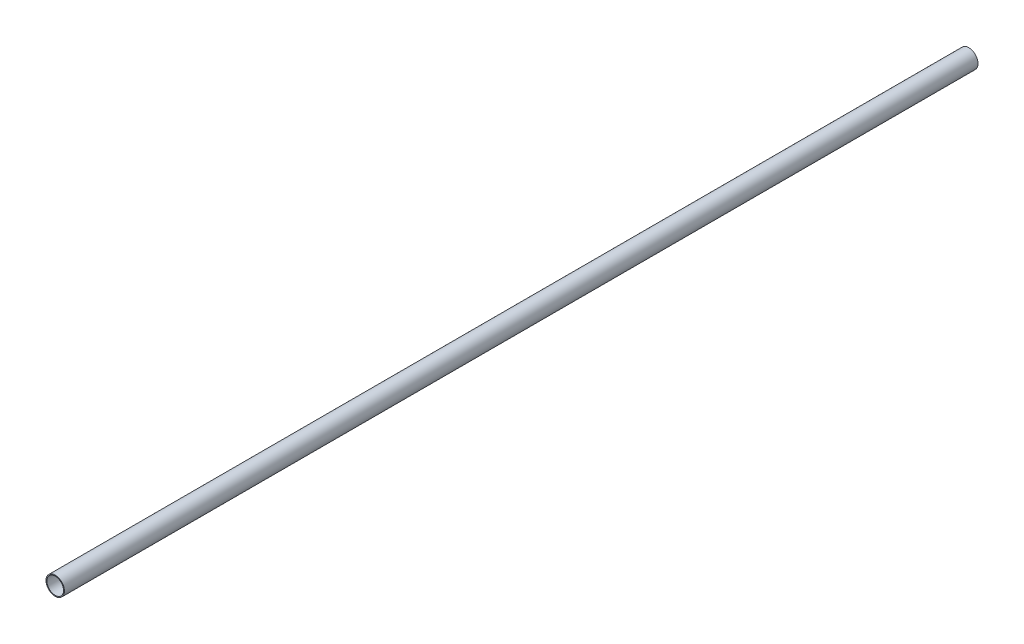
SolidWorks part; units mm, degrees
ref_plane "front" through (0, 0, 0) normal (0, 0, 1) x (1, 0, 0)
ref_plane "top" through (0, 0, 0) normal (0, 1, 0) x (1, 0, 0)
ref_plane "right" through (0, 0, 0) normal (1, 0, 0) x (0, 0, -1)
sketch "Sketch1" plane through (0, 0, 0) normal (0, 0, 1) x (1, 0, 0)
  circle A0 centre (0, 0) radius 25.4
  circle A1 centre (0, 0) radius 22.987
  dimension "D1" = 50.8
  dimension "D2" = 2.413
extrude "Extrude1" add sketch "Sketch1" along normal mid plane 2519.4006
